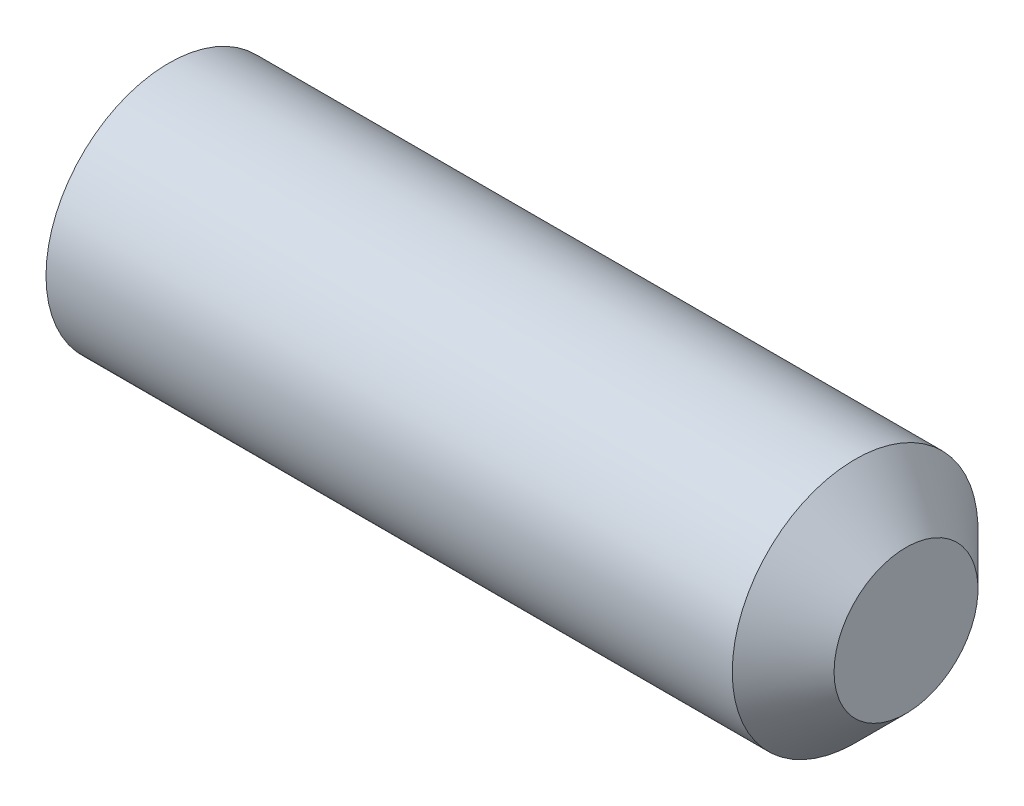
SolidWorks part; units mm, degrees
material "AISI 304"
ref_plane "Front Plane" through (0, 0, 0) normal (0, 0, 1) x (1, 0, 0)
ref_plane "Top Plane" through (0, 0, 0) normal (0, 1, 0) x (1, 0, 0)
ref_plane "Right Plane" through (0, 0, 0) normal (1, 0, 0) x (0, 0, -1)
sketch "Sketch1" plane through (0, 0, 0) normal (0, 0, 1) x (1, 0, 0)
  line L0 (0, 0) -> (105.4919, 0) construction
  line L1 (30, 2.9289) -> (30, 0)
  line L2 (30, 2.9289) -> (27.9289, 5)
  line L3 (27.9289, 5) -> (0, 5)
  line L4 (0, 5) -> (0, 0)
  line L5 (0, 0) -> (30, 0)
  dimension "D1" = 10
  dimension "D2" = 30
  dimension "D3" = 45
  dimension "D4" = 90
revolve "Revolve1" add sketch "Sketch1" angle 360 about L0
sketch "Sketch2" plane through (0, 0, 0) normal (-1, 0, 0) x (0, 0, 1)
  line L1 (-1.4434, 2.5) -> (-2.8868, 0)
  line L2 (-2.8868, 0) -> (-1.4434, -2.5)
  line L3 (-1.4434, -2.5) -> (1.4434, -2.5)
  line L4 (1.4434, -2.5) -> (2.8868, 0)
  line L5 (2.8868, 0) -> (1.4434, 2.5)
  line L6 (1.4434, 2.5) -> (-1.4434, 2.5)
  circle A0 centre (0, 0) radius 2.5 construction
  dimension "D1" = 5
extrude "Cut-Extrude1" cut sketch "Sketch2" against normal blind 3
